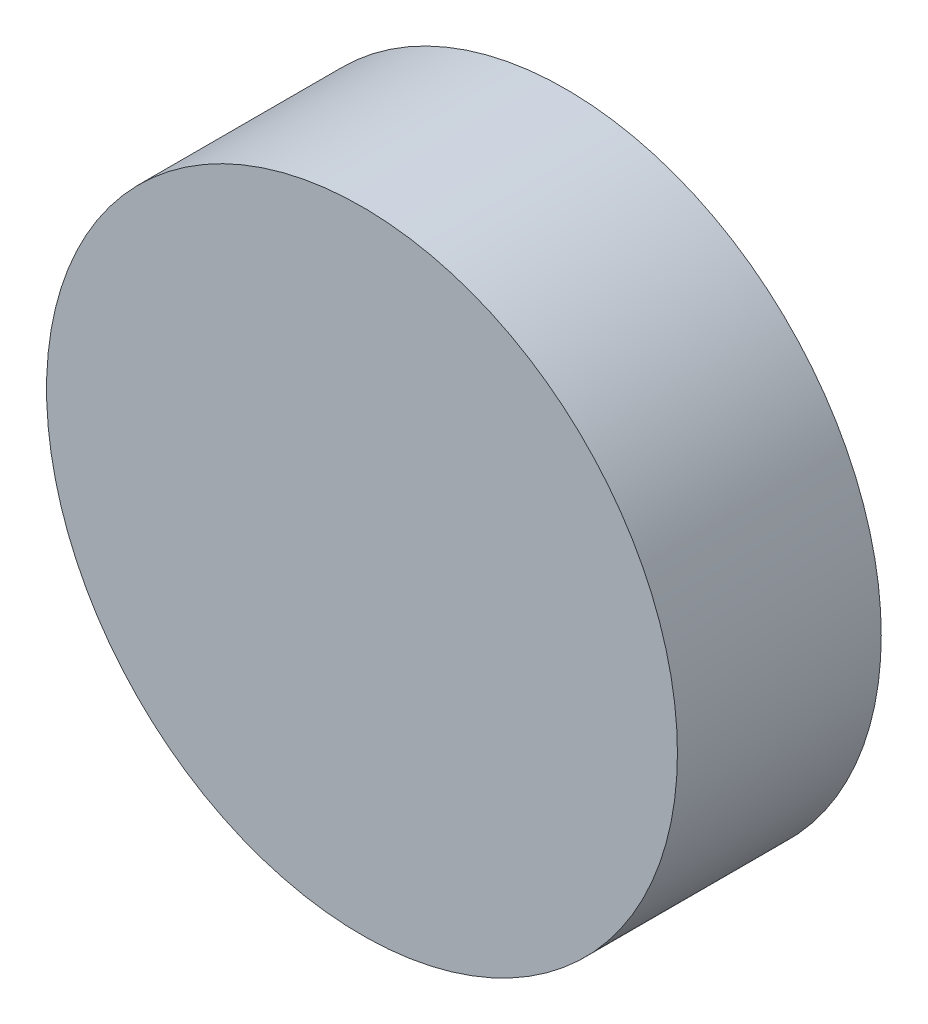
SolidWorks part; units mm, degrees
ref_plane "Face" through (0, 0, 0) normal (0, 0, 1) x (1, 0, 0)
ref_plane "Dessus" through (0, 0, 0) normal (0, 1, 0) x (1, 0, 0)
ref_plane "Droite" through (0, 0, 0) normal (1, 0, 0) x (0, 0, -1)
sketch "Esquisse1" plane through (0, 0, 0) normal (0, 0, 1) x (1, 0, 0)
  circle A0 centre (0, 0) radius 6.5
  circle A1 centre (0, 0) radius 4.5
  dimension "D1" = 9
  dimension "D2" = 13
extrude "Base-Extrusion" add sketch "Esquisse1" along normal blind 4
sketch "Esquisse2" plane through (0, 0, 4) normal (0, 0, 1) x (1, 0, 0)
  circle A0 centre (0, 0) radius 6.5 construction
  circle A1 centre (0, 0) radius 6.5
extrude "Boss.-Extru.1" add sketch "Esquisse2" along normal blind 0.2
